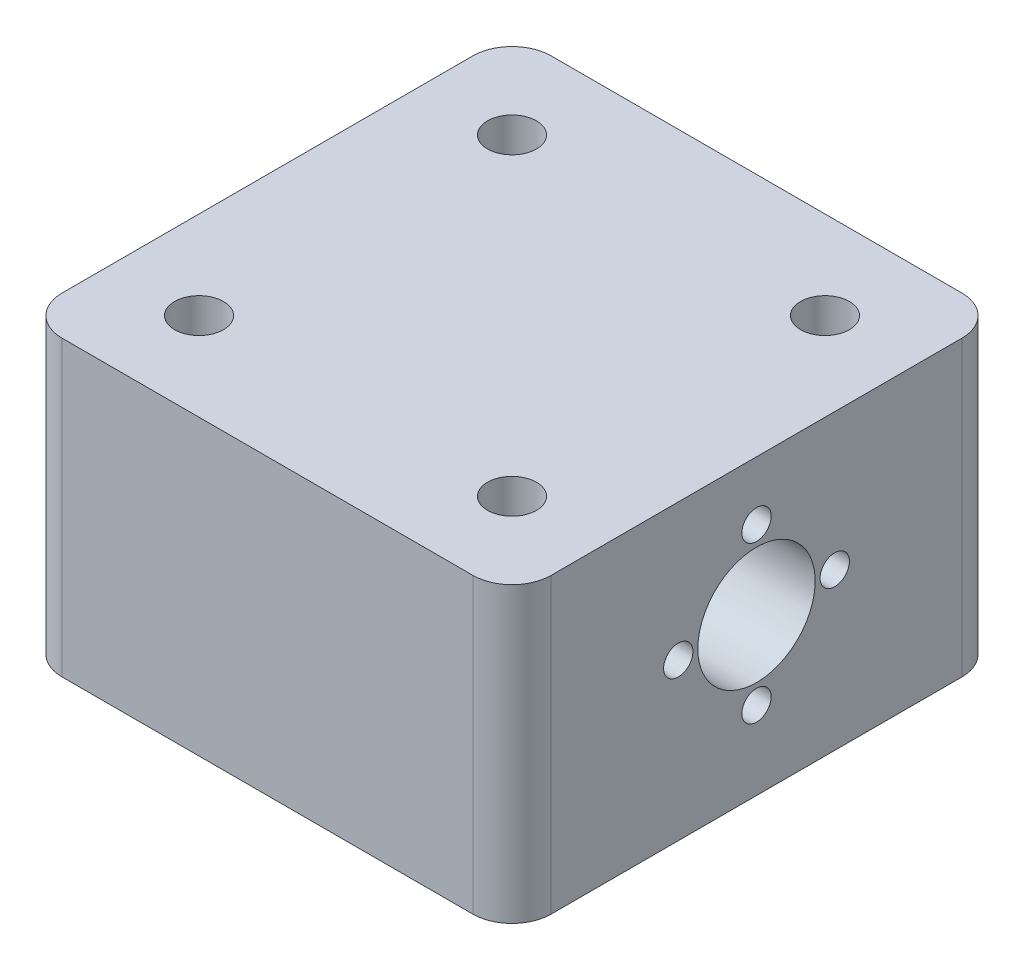
SolidWorks part; units mm, degrees
ref_plane "Front Plane" through (0, 0, 0) normal (0, 0, 1) x (1, 0, 0)
ref_plane "Top Plane" through (0, 0, 0) normal (0, 1, 0) x (1, 0, 0)
ref_plane "Right Plane" through (0, 0, 0) normal (1, 0, 0) x (0, 0, -1)
sketch "Sketch1" plane through (0, 0, 0) normal (0, 1, 0) x (1, 0, 0)
  line L1 (-25, 25) -> (25, 25)
  line L2 (-25, 25) -> (-25, -25)
  line L3 (-25, -25) -> (25, -25)
  line L4 (25, 25) -> (25, -25)
  line L5 (-25, 25) -> (25, -25) construction
  line L6 (-25, -25) -> (25, 25) construction
  point P0 (0, 0)
  dimension "D1" = 50
  dimension "D2" = 50
extrude "Boss-Extrude1" add sketch "Sketch1" along normal blind 30
sketch "Sketch2" plane through (0, 0, 0) normal (0, -1, 0) x (1, 0, 0)
  circle A0 centre (0, 10) radius 2.5
  circle A1 centre (0, -10) radius 2.5
  circle A2 centre (10, 0) radius 2.5
  circle A3 centre (-10, 0) radius 2.5
  circle A4 centre (0, 0) radius 2.5
  dimension "D1" = 5
  dimension "D2" = 5
  dimension "D3" = 5
  dimension "D4" = 5
  dimension "D9" = 5
  dimension "D5" = 20
  dimension "D6" = 20
  dimension "D7" = 10
  dimension "D8" = 10
extrude "Cut-Extrude1" cut sketch "Sketch2" against normal blind 15
sketch "Sketch4" plane through (-25, 0, 0) normal (-1, 0, 0) x (0, 0, 1)
  line L0 (-25, 0) -> (25, 0) construction
  circle A0 centre (0, 16) radius 6
  dimension "D1" = 12
  dimension "D2" = 16
extrude "Cut-Extrude2" cut sketch "Sketch4" against normal up to next
sketch "Sketch5" plane through (-25, 0, 0) normal (-1, 0, 0) x (0, 0, 1)
  circle A0 centre (-8, 16) radius 1.5
  circle A1 centre (8, 16) radius 1.5
  circle A2 centre (0, 8) radius 1.5
  circle A3 centre (0, 24) radius 1.5
  point P15 (0, 16)
  dimension "D5" = 3
  dimension "D6" = 3
  dimension "D7" = 3
  dimension "D8" = 3
  dimension "D1" = 16
  dimension "D2" = 16
  dimension "D3" = 8
  dimension "D4" = 8
extrude "Cut-Extrude3" cut sketch "Sketch5" against normal blind 10
sketch "Sketch6" plane through (25, 0, 0) normal (1, 0, 0) x (0, 0, -1)
  circle A0 centre (-8, 16) radius 1.5
  circle A1 centre (8, 16) radius 1.5
  circle A2 centre (0, 24) radius 1.5
  circle A3 centre (0, 8) radius 1.5
  circle A4 centre (0, 16) radius 6 construction
  point P11 (0, 16)
  dimension "D1" = 3
  dimension "D2" = 3
  dimension "D3" = 3
  dimension "D4" = 3
  dimension "D5" = 16
  dimension "D6" = 16
  dimension "D7" = 8
  dimension "D8" = 8
extrude "Cut-Extrude4" cut sketch "Sketch6" against normal blind 10 contours A2 | A0 | A3 | A1
fillet "Fillet1" radius 4 4 edges at (25, 15, 25) (-25, 15, 25) (-25, 15, -25) (25, 15, -25)
sketch "Sketch8" plane through (0, 30, 0) normal (0, 1, 0) x (1, 0, 0)
  circle A0 centre (-16, 16) radius 2.5
  circle A1 centre (16, 16) radius 2.5
  circle A2 centre (16, -16) radius 2.5
  circle A3 centre (-16, -16) radius 2.5
  dimension "D1" = 5
  dimension "D2" = 5
  dimension "D3" = 5
  dimension "D4" = 5
  dimension "D5" = 32
  dimension "D6" = 32
  dimension "D7" = 16
  dimension "D8" = 16
extrude "Cut-Extrude5" cut sketch "Sketch8" against normal blind 15
